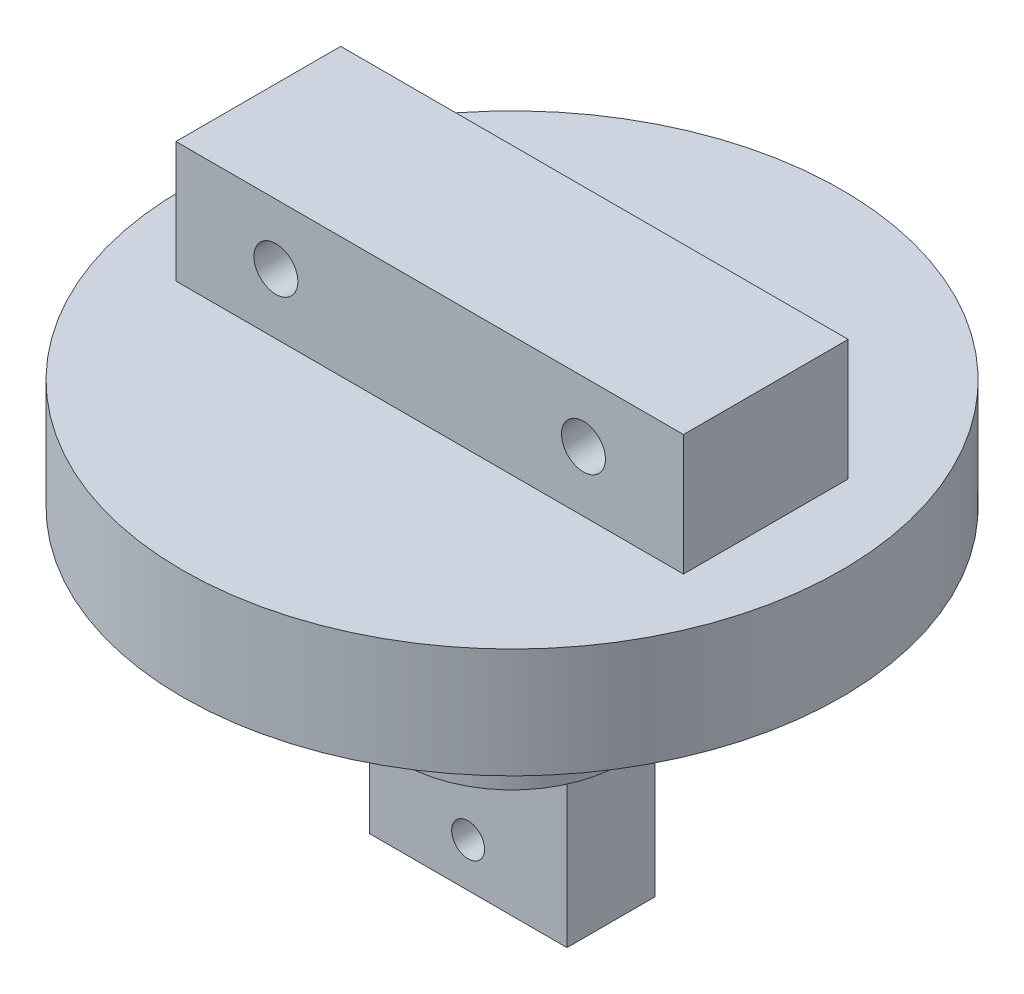
SolidWorks part; units mm, degrees
ref_plane "Front Plane" through (0, 0, 0) normal (0, 0, 1) x (1, 0, 0)
ref_plane "Top Plane" through (0, 0, 0) normal (0, 1, 0) x (1, 0, 0)
ref_plane "Right Plane" through (0, 0, 0) normal (1, 0, 0) x (0, 0, -1)
sketch "Sketch1" plane through (0, 0, 0) normal (0, 1, 0) x (1, 0, 0)
  circle A0 centre (0, 0) radius 30
extrude "Boss-Extrude1" add sketch "Sketch1" along normal blind 10
sketch "Sketch2" plane through (0, 0, 0) normal (0, -1, 0) x (-1, 0, 0)
  circle A0 centre (0, 0) radius 10
extrude "Boss-Extrude2" add sketch "Sketch2" along normal blind 15.25
sketch "Sketch3" plane through (0, -15.25, 0) normal (0, -1, 0) x (-1, 0, 0)
  line L0 (0, 0) -> (-9, 0)
  line L1 (-9, 0) -> (-9, 4)
  line L2 (-9, 4) -> (9, 4)
  line L3 (9, 4) -> (9, -4)
  line L4 (9, -4) -> (-9, -4)
  line L5 (-9, -4) -> (-9, 0)
  dimension "D1" = 4
  dimension "D2" = 18
  dimension "D3" = 9
  dimension "D4" = 8
extrude "Boss-Extrude3" add sketch "Sketch3" along normal blind 13
hole_wizard "Ø3.0 (3) Diameter Hole1" positions "Sketch6" profile "Sketch7" hole size "Ø3.0" standard "ISO" end condition through all
sketch "Sketch6" plane through (0, 0, 4) normal (0, 0, 1) x (1, 0, 0)
  line L0 (-9, -15.25) -> (9, -15.25) construction
  point P0 (0, -24.25)
  point P2 (0, -18.25)
  point P7 (0, -15.25)
  dimension "D1" = 3
  dimension "D2" = 6
sketch "Sketch7" plane through (0, -24.25, 4) normal (1, 0, 0) x (0, -1, 0)
  line L0 (0, 0) -> (0, 34)
  line L1 (0, 34) -> (1.5, 34)
  line L2 (1.5, 34) -> (1.5, 0)
  line L5 (1.5, 0) -> (0, 0)
  line L11 (0, -6.35) -> (0, 107.95) construction
  dimension "Thru Hole Dia." = 3
  dimension "Thru Hole Depth" = 34
sketch "Sketch8" plane through (0, 10, 0) normal (0, 1, 0) x (1, 0, 0)
  line L1 (-23.1, 0) -> (-23.1, 7.5)
  line L2 (-23.1, 7.5) -> (23.1, 7.5)
  line L3 (23.1, 7.5) -> (23.1, -7.5)
  line L4 (23.1, -7.5) -> (-23.1, -7.5)
  line L5 (-23.1, -7.5) -> (-23.1, 0)
  point P8 (0, -7.5)
  dimension "D4" = 0
  dimension "D1" = 7.5
  dimension "D2" = 15
  dimension "D3" = 46.2
extrude "Boss-Extrude4" add sketch "Sketch8" along normal blind 11 contours L5 L4 L3 L2 L1
hole_wizard "Ø4.0 (4) Diameter Hole1" positions "Sketch9" profile "Sketch10" hole size "Ø4.0" standard "ISO" end condition up to next
sketch "Sketch9" plane through (0, 0, -7.5) normal (0, 0, -1) x (-1, 0, 0)
  line L0 (23.1, 15.5) -> (14, 15.5)
  line L1 (23.1, 21) -> (23.1, 10) construction
  line L2 (14, 15.5) -> (-14, 15.5)
  line L4 (-23.1, 21) -> (-23.1, 10) construction
  point P2 (14, 15.5)
  point P6 (-14, 15.5)
  dimension "D1" = 9.1
  dimension "D2" = 28
  dimension "D3" = 5.5
  dimension "D4" = 9.1
sketch "Sketch10" plane through (14, 15.5, -7.5) normal (1, 0, 0) x (0, 1, 0)
  line L0 (0, 0) -> (0, 15)
  line L1 (0, 15) -> (2, 15)
  line L2 (2, 15) -> (2, 0)
  line L5 (2, 0) -> (0, 0)
  line L11 (0, -6.35) -> (0, 107.95) construction
  dimension "Thru Hole Dia." = 4
  dimension "Thru Hole Depth" = 15
